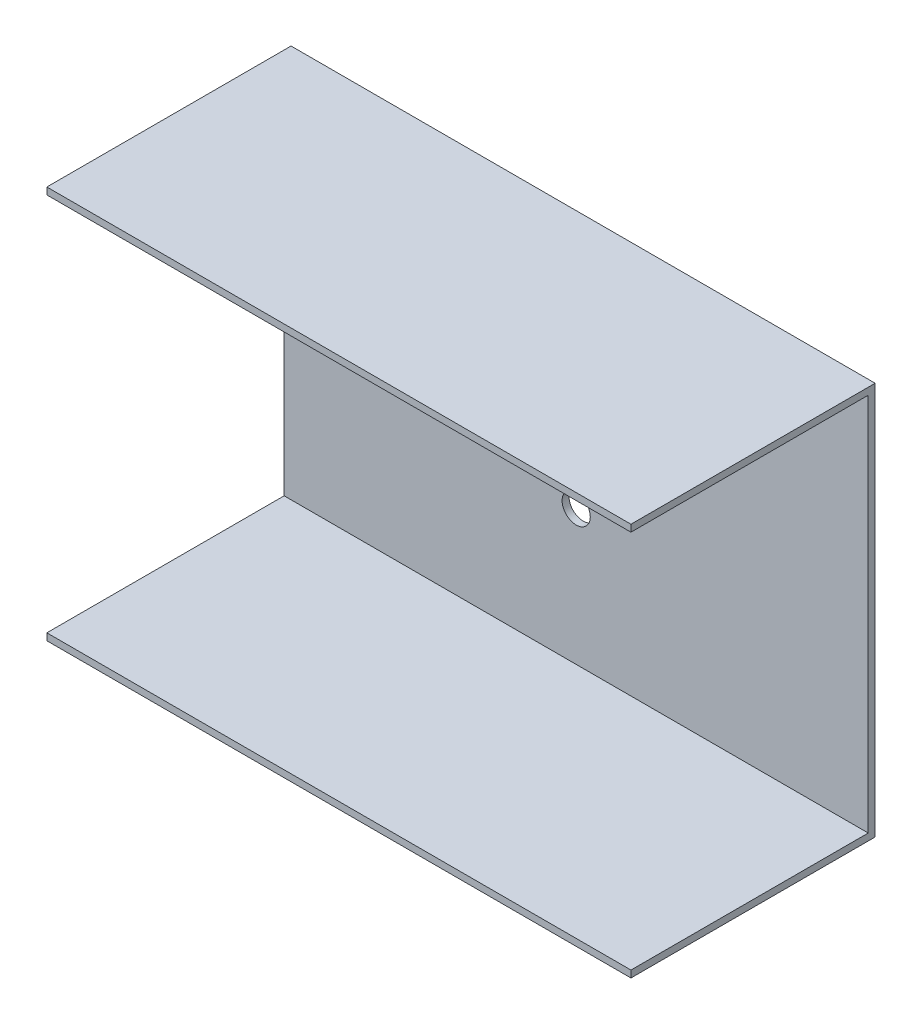
SolidWorks part; units mm, degrees
ref_plane "Front Plane" through (0, 0, 0) normal (0, 0, 1) x (1, 0, 0)
ref_plane "Top Plane" through (0, 0, 0) normal (0, 1, 0) x (1, 0, 0)
ref_plane "Right Plane" through (0, 0, 0) normal (1, 0, 0) x (0, 0, -1)
sketch "Sketch1" plane through (0, 0, 0) normal (1, 0, 0) x (0, 0, -1)
  line L0 (0, 0) -> (0, -1.6002)
  line L1 (0, -1.6002) -> (55, -1.6002)
  line L2 (55, -1.6002) -> (55, -89.4909)
  line L3 (55, -89.4909) -> (0, -89.4909)
  line L4 (0, -89.4909) -> (0, -91.0911)
  line L5 (0, -91.0911) -> (56.6002, -91.0911)
  line L6 (56.6002, -91.0911) -> (56.6002, 0)
  line L7 (56.6002, 0) -> (0, 0)
  line L8 (55, -1.6002) -> (56.6002, -1.6002) construction
  dimension "D1" = 91.0911
  dimension "D2" = 1.6002
  dimension "D3" = 55
extrude "Boss-Extrude1" add sketch "Sketch1" along normal blind 135.3879
sketch "Sketch2" plane through (0, 0, -55) normal (0, 0, 1) x (1, 0, 0)
  line L0 (67.694, -32.8455) -> (67.694, -58.2455) construction
  line L1 (54.994, -45.5455) -> (80.394, -45.5455) construction
  line L2 (0, -45.5455) -> (135.3879, -45.5455) construction
  line L3 (0, -1.6002) -> (0, -89.4909) construction
  line L4 (135.3879, -1.6002) -> (135.3879, -89.4909) construction
  line L5 (67.694, -1.6002) -> (67.694, -89.4909) construction
  line L6 (135.3879, -1.6002) -> (0, -1.6002) construction
  line L7 (135.3879, -89.4909) -> (0, -89.4909) construction
  circle A0 centre (67.694, -32.8455) radius 3.2639
  circle A1 centre (67.694, -58.2455) radius 3.2639
  circle A2 centre (54.994, -45.5455) radius 3.2639
  circle A3 centre (80.394, -45.5455) radius 3.2639
  point P9 (67.694, -45.5455)
  dimension "D1" = 6.5278
  dimension "D2" = 25.4
extrude "Cut-Extrude1" cut sketch "Sketch2" against normal up to surface (1.6002 mm away) up to face at (67.694, -45.5455, -56.6002)
